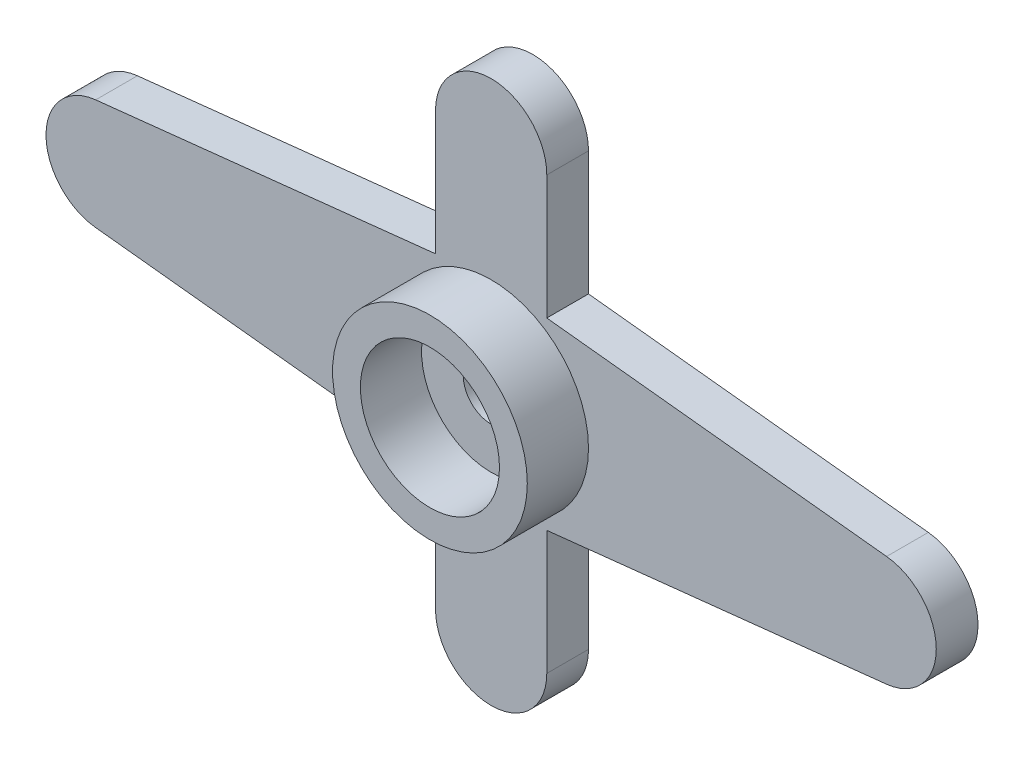
SolidWorks part; units mm, degrees
ref_plane "Front Plane" through (0, 0, 0) normal (0, 0, 1) x (1, 0, 0)
ref_plane "Top Plane" through (0, 0, 0) normal (0, 1, 0) x (1, 0, 0)
ref_plane "Right Plane" through (0, 0, 0) normal (1, 0, 0) x (0, 0, -1)
sketch "Sketch1" plane through (0, 0, 0) normal (0, 0, 1) x (1, 0, 0)
  line L0 (0, 0) -> (0, 10.3254) construction
  line L1 (0, 0) -> (16, 0) construction
  line L2 (2, 7.7586) -> (2, 3.3047)
  line L3 (2, 3.3047) -> (14.2143, 1.9885)
  line L4 (2, -3.3047) -> (14.2143, -1.9885)
  line L5 (2, -7.7586) -> (2, -3.3047)
  line L6 (-2, -7.7586) -> (-2, -3.3047)
  line L7 (-2, -3.3047) -> (-14.2143, -1.9885)
  line L8 (-2, 3.3047) -> (-14.2143, 1.9885)
  line L9 (-2, 7.7586) -> (-2, 3.3047)
  arc A0 (3.5, 0) -> (0, 3.5) centre (0, 0) ccw construction
  arc A1 (2.5, 0) -> (0, 2.5) centre (0, 0) ccw construction
  arc A2 (14.2143, -1.9885) -> (14.2143, 1.9885) centre (14, 0) ccw
  arc A3 (2, 7.7586) -> (-2, 7.7586) centre (0, 7.7586) ccw
  arc A4 (2, -7.7586) -> (-2, -7.7586) centre (0, -7.7586) cw
  arc A5 (-14.2143, -1.9885) -> (-14.2143, 1.9885) centre (-14, 0) cw
  dimension "D1" = 7
  dimension "D2" = 5
  dimension "D3" = 4
  dimension "D4" = 4
extrude "Boss-Extrude1" add sketch "Sketch1" along normal blind 1.5
sketch "Sketch2" plane through (0, 0, 1.5) normal (0, 0, 1) x (1, 0, 0)
  circle A0 centre (0, 0) radius 3.5
  circle A1 centre (0, 0) radius 2.5
  dimension "D1" = 7
  dimension "D2" = 5
extrude "Boss-Extrude2" add sketch "Sketch2" along normal blind 2.2
sketch "Sketch3" plane through (0, 0, 1.5) normal (0, 0, 1) x (1, 0, 0)
  circle A0 centre (0, 0) radius 1
  dimension "D1" = 2
extrude "Cut-Extrude1" cut sketch "Sketch3" against normal up to next
sketch "Sketch4" plane through (0, 0, 0) normal (0, 0, -1) x (-1, 0, 0)
  circle A0 centre (0, 0) radius 2.5
  dimension "D1" = 5
extrude "Cut-Extrude2" cut sketch "Sketch4" against normal blind 1
